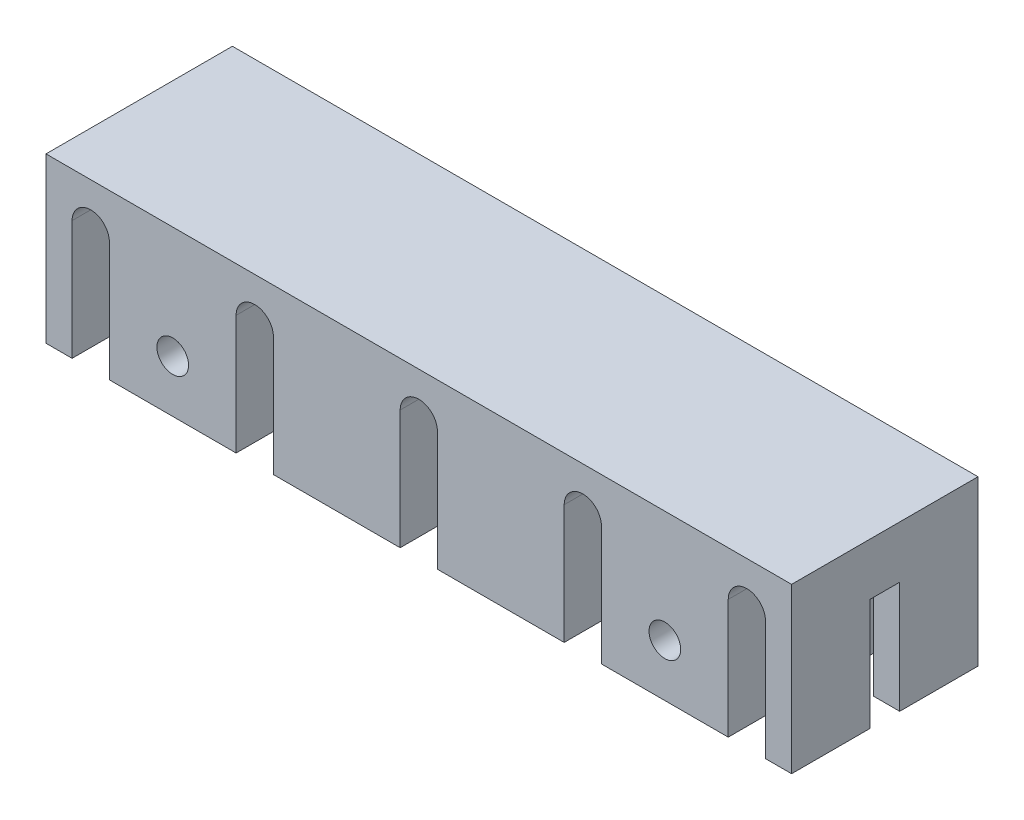
SolidWorks part; units mm, degrees
ref_plane "Front Plane" through (0, 0, 0) normal (0, 0, 1) x (1, 0, 0)
ref_plane "Top Plane" through (0, 0, 0) normal (0, 1, 0) x (1, 0, 0)
ref_plane "Right Plane" through (0, 0, 0) normal (1, 0, 0) x (0, 0, -1)
sketch "Sketch1" plane through (0, 0, 0) normal (0, 1, 0) x (1, 0, 0)
  line L1 (-50, -12.5) -> (50, -12.5)
  line L2 (-50, -12.5) -> (-50, 12.5)
  line L3 (-50, 12.5) -> (50, 12.5)
  line L4 (50, -12.5) -> (50, 12.5)
  line L5 (-50, -12.5) -> (50, 12.5) construction
  line L6 (-50, 12.5) -> (50, -12.5) construction
  point P0 (0, 0)
  dimension "D1" = 100
  dimension "D2" = 25
extrude "Boss-Extrude1" add sketch "Sketch1" along normal blind 25
sketch "Sketch2" plane through (0, 0, 12.5) normal (0, 0, 1) x (1, 0, 0)
  line L0 (-50, 25) -> (-50, 0) construction
  line L1 (-50, 25) -> (50, 25) construction
  line L2 (-50, 0) -> (50, 0) construction
  line L3 (-19.5, 19) -> (-19.5, 0)
  line L4 (-46.5, 19) -> (-46.5, 0)
  line L5 (-46.5, 0) -> (-41.5, 0)
  line L6 (-41.5, 19) -> (-41.5, 0)
  line L7 (-24.5, 19) -> (-24.5, 0)
  line L8 (-24.5, 0) -> (-19.5, 0)
  line L9 (2.5, 19) -> (2.5, 0)
  line L10 (-2.5, 19) -> (-2.5, 0)
  line L11 (-2.5, 0) -> (2.5, 0)
  line L12 (24.5, 19) -> (24.5, 0)
  line L13 (19.5, 19) -> (19.5, 0)
  line L14 (19.5, 0) -> (24.5, 0)
  line L15 (46.5, 19) -> (46.5, 0)
  line L16 (41.5, 19) -> (41.5, 0)
  line L17 (41.5, 0) -> (46.5, 0)
  arc A0 (-41.5, 19) -> (-46.5, 19) centre (-44, 19) ccw
  arc A1 (-19.5, 19) -> (-24.5, 19) centre (-22, 19) ccw
  arc A2 (2.5, 19) -> (-2.5, 19) centre (0, 19) ccw
  arc A3 (24.5, 19) -> (19.5, 19) centre (22, 19) ccw
  arc A4 (46.5, 19) -> (41.5, 19) centre (44, 19) ccw
  dimension "D1" = 5
  dimension "D2" = 6
  dimension "D3" = 6
  dimension "D4" = 5
extrude "Cut-Extrude1" cut sketch "Sketch2" against normal blind 48
sketch "Sketch3" plane through (-50, 0, 0) normal (-1, 0, 0) x (0, 0, 1)
  line L0 (0, 25) -> (0, 0) construction
  line L1 (-12.5, 25) -> (12.5, 25) construction
  line L2 (-12.5, 0) -> (12.5, 0) construction
  line L4 (-2, 18) -> (2, 18)
  line L5 (-2, 18) -> (-2, 0)
  line L6 (-2, 0) -> (2, 0)
  line L7 (2, 18) -> (2, 0)
  line L8 (-2, 18) -> (2, 0) construction
  line L9 (-2, 0) -> (2, 18) construction
  point P6 (0, 9)
  dimension "D1" = 18
  dimension "D2" = 4
extrude "Cut-Extrude2" cut sketch "Sketch3" against normal through all
sketch "Sketch4" plane through (0, 0, 12.5) normal (0, 0, 1) x (1, 0, 0)
  line L0 (0, 25) -> (0, -35.6184) construction
  line L1 (-50, 25) -> (50, 25) construction
  line L2 (-41.5, 0) -> (-24.5, 0) construction
  line L3 (-33, 0) -> (-33, 25) construction
  circle A0 centre (-33, 10) radius 2.1224
  circle A1 centre (33, 10) radius 2.1224
  dimension "D1" = 10
  dimension "D2" = 0
extrude "Cut-Extrude3" cut sketch "Sketch4" against normal through all
sketch "Sketch5" plane through (0, 0, 12.5) normal (0, 0, 1) x (1, 0, 0)
  line L0 (50, 25) -> (50, 0) construction
  line L1 (-50, 0) -> (50, 0)
  line L2 (-50, 0) -> (-50, 3)
  line L3 (-50, 3) -> (50, 3)
  line L4 (50, 0) -> (50, 3)
  dimension "D1" = 3
extrude "Cut-Extrude4" cut sketch "Sketch5" against normal through all
